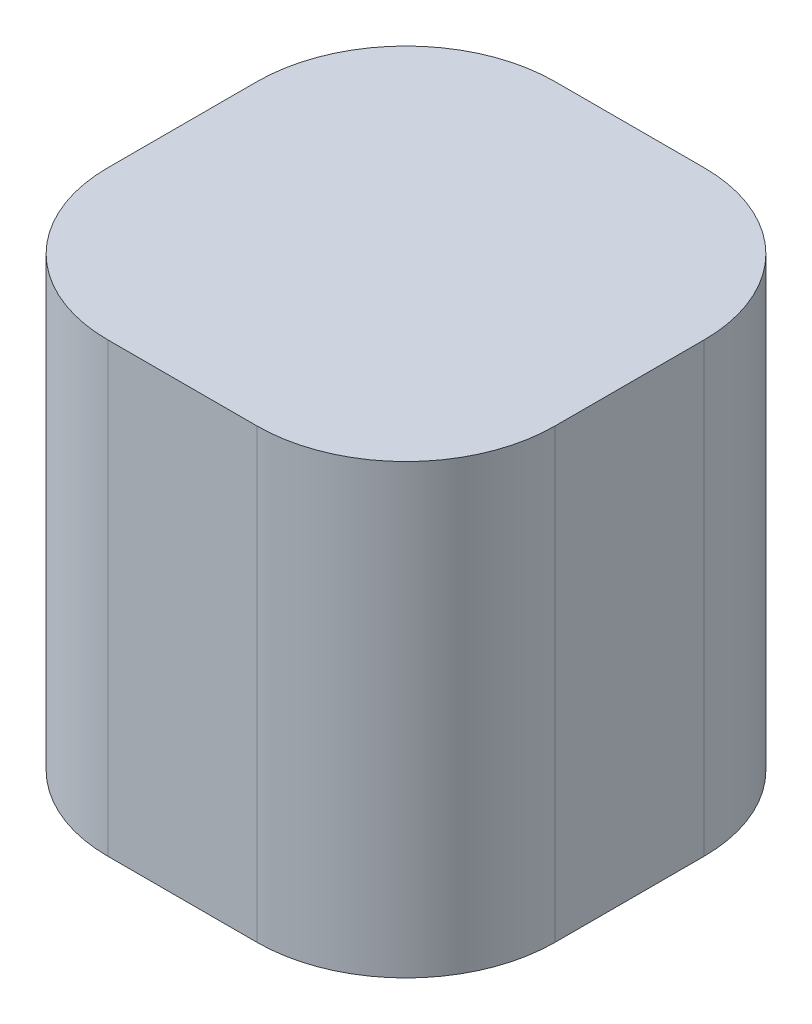
SolidWorks part; units mm, degrees
ref_plane "Спереди" through (0, 0, 0) normal (0, 0, 1) x (1, 0, 0)
ref_plane "Сверху" through (0, 0, 0) normal (0, 1, 0) x (1, 0, 0)
ref_plane "Справа" through (0, 0, 0) normal (1, 0, 0) x (0, 0, -1)
sketch "Sketch1" plane through (0, 0, 0) normal (0, 1, 0) x (1, 0, 0)
  line L1 (3, -3) -> (-3, -3)
  line L2 (3, -3) -> (3, 3)
  line L3 (3, 3) -> (-3, 3)
  line L4 (-3, -3) -> (-3, 3)
  line L5 (3, -3) -> (-3, 3) construction
  line L6 (3, 3) -> (-3, -3) construction
  point P0 (0, 0)
  dimension "D1" = 6
extrude "Boss-Extrude1" add sketch "Sketch1" along normal blind 6
sketch "Sketch2" plane through (0, 0, 0) normal (0, -1, 0) x (1, 0, 0)
  line L1 (1, -1) -> (-1, -1)
  line L2 (1, -1) -> (1, 1)
  line L3 (1, 1) -> (-1, 1)
  line L4 (-1, -1) -> (-1, 1)
  line L5 (1, -1) -> (-1, 1) construction
  line L6 (1, 1) -> (-1, -1) construction
  point P0 (0, 0)
  dimension "D1" = 2
extrude "Cut-Extrude1" cut sketch "Sketch2" against normal blind 2.5
fillet "Fillet1" radius 2 4 edges at (-3, 3, -3) (3, 3, -3) (3, 3, 3) (-3, 3, 3)
chamfer "Chamfer1" distance 0.3 angle 60 4 edges at (-1, 0, 0) (0, 0, 1) (1, 0, 0) (0, 0, -1)
